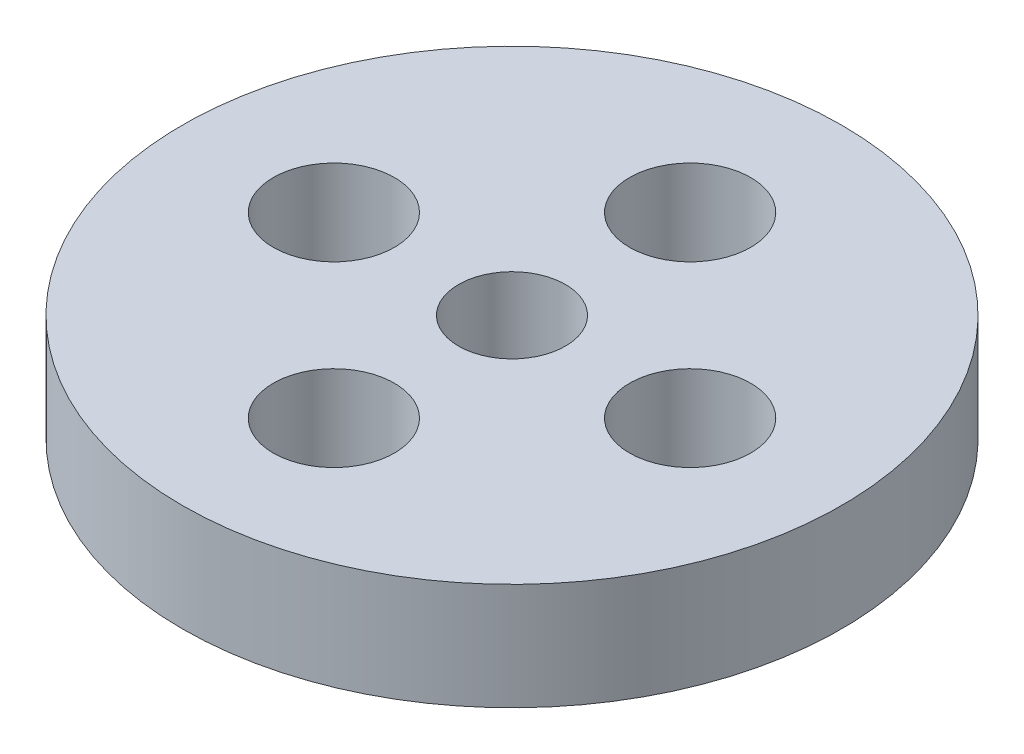
SolidWorks part; units mm, degrees
material "3DP Resin"
ref_plane "Front Plane" through (0, 0, 0) normal (0, 0, 1) x (1, 0, 0)
ref_plane "Top Plane" through (0, 0, 0) normal (0, 1, 0) x (1, 0, 0)
ref_plane "Right Plane" through (0, 0, 0) normal (1, 0, 0) x (0, 0, -1)
sketch "Sketch1" plane through (0, 0, 0) normal (0, 1, 0) x (1, 0, 0)
  line L0 (0, 9.25) -> (0, -9.25) construction
  line L1 (-9.25, 0) -> (9.25, 0) construction
  circle A0 centre (0, 0) radius 9.25
  circle A1 centre (-5, 0) radius 1.7
  circle A2 centre (0, 5) radius 1.7
  circle A3 centre (5, 0) radius 1.7
  circle A4 centre (0, -5) radius 1.7
  circle A5 centre (0, 0) radius 1.5
  point P18 (0, 0)
  dimension "D1" = 18.5
  dimension "D2" = 3.4
  dimension "D5" = 3
  dimension "D3" = 5
  dimension "D4" = 4
extrude "Boss-Extrude1" add sketch "Sketch1" along normal blind 3
